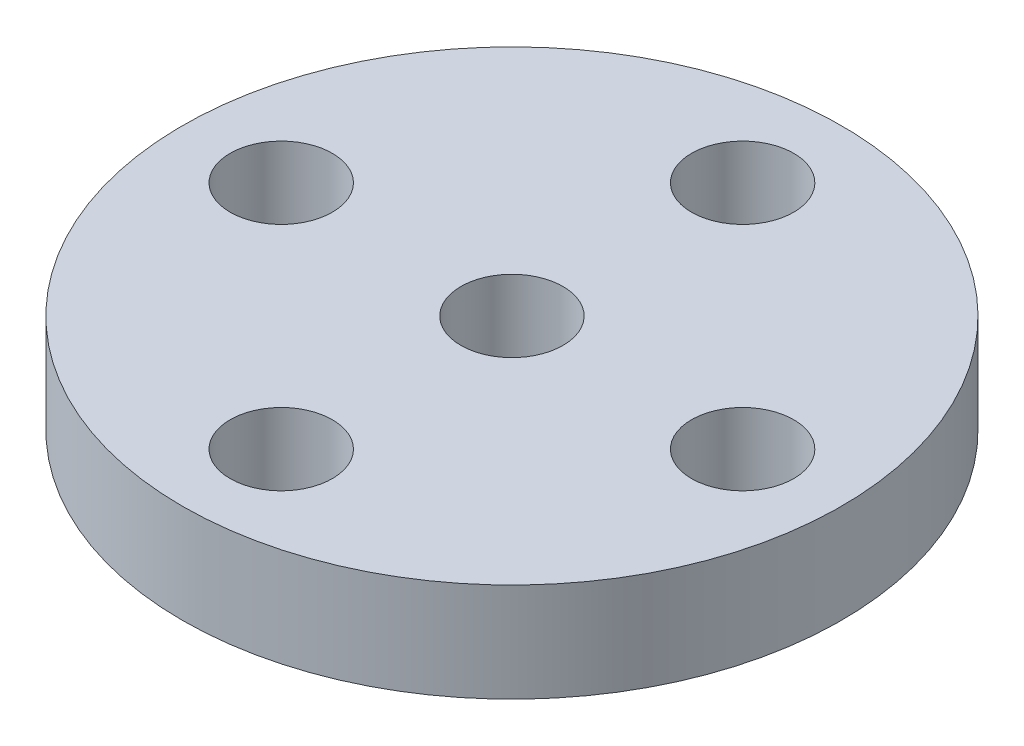
SolidWorks part; units mm, degrees
ref_plane "前视基准面" through (0, 0, 0) normal (0, 0, 1) x (1, 0, 0)
ref_plane "上视基准面" through (0, 0, 0) normal (0, 1, 0) x (1, 0, 0)
ref_plane "右视基准面" through (0, 0, 0) normal (1, 0, 0) x (0, 0, -1)
sketch "草图1" plane through (0, 0, 0) normal (0, 1, 0) x (1, 0, 0)
  circle A0 centre (0, 0) radius 1.55
  circle A1 centre (0, 0) radius 4
  dimension "D1" = 3.1
  dimension "D2" = 8
extrude "凸台-拉伸1" add sketch "草图1" along normal blind 4
ref_plane "基准面1" through (0, 4, 0) normal (0, 1, 0) x (1, 0, 0)
sketch "草图2" plane through (0, 4, 0) normal (0, 1, 0) x (1, 0, 0)
  circle A0 centre (0, 0) radius 1.55
  circle A1 centre (0, 0) radius 7 construction
  circle A2 centre (0, 0) radius 10
  circle A3 centre (0, 7) radius 1.55
  circle A4 centre (7, 0) radius 1.55
  circle A5 centre (0, -7) radius 1.55
  circle A6 centre (-7, 0) radius 1.55
  point P16 (0, 0)
  dimension "D1" = 14
  dimension "D2" = 20
  dimension "D3" = 3.1
  dimension "D4" = 4
extrude "凸台-拉伸2" add sketch "草图2" along normal blind 3
